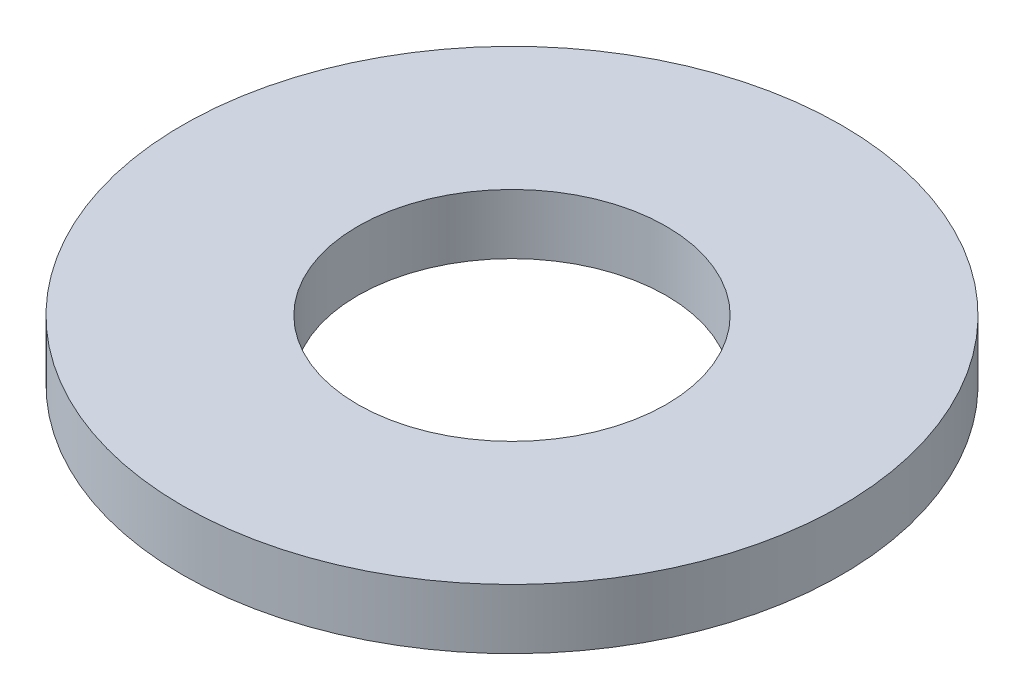
SolidWorks part; units mm, degrees
material "6061-T6 (SS)"
ref_plane "Front Plane" through (0, 0, 0) normal (0, 0, 1) x (1, 0, 0)
ref_plane "Top Plane" through (0, 0, 0) normal (0, 1, 0) x (1, 0, 0)
ref_plane "Right Plane" through (0, 0, 0) normal (1, 0, 0) x (0, 0, -1)
sketch "Sketch1" plane through (0, 0, 0) normal (0, 1, 0) x (1, 0, 0)
  circle A0 centre (0, 0) radius 5.15
  circle A1 centre (0, 0) radius 11
  dimension "D1" = 10.3
  dimension "D2" = 22
extrude "Boss-Extrude1" add sketch "Sketch1" along normal blind 2
